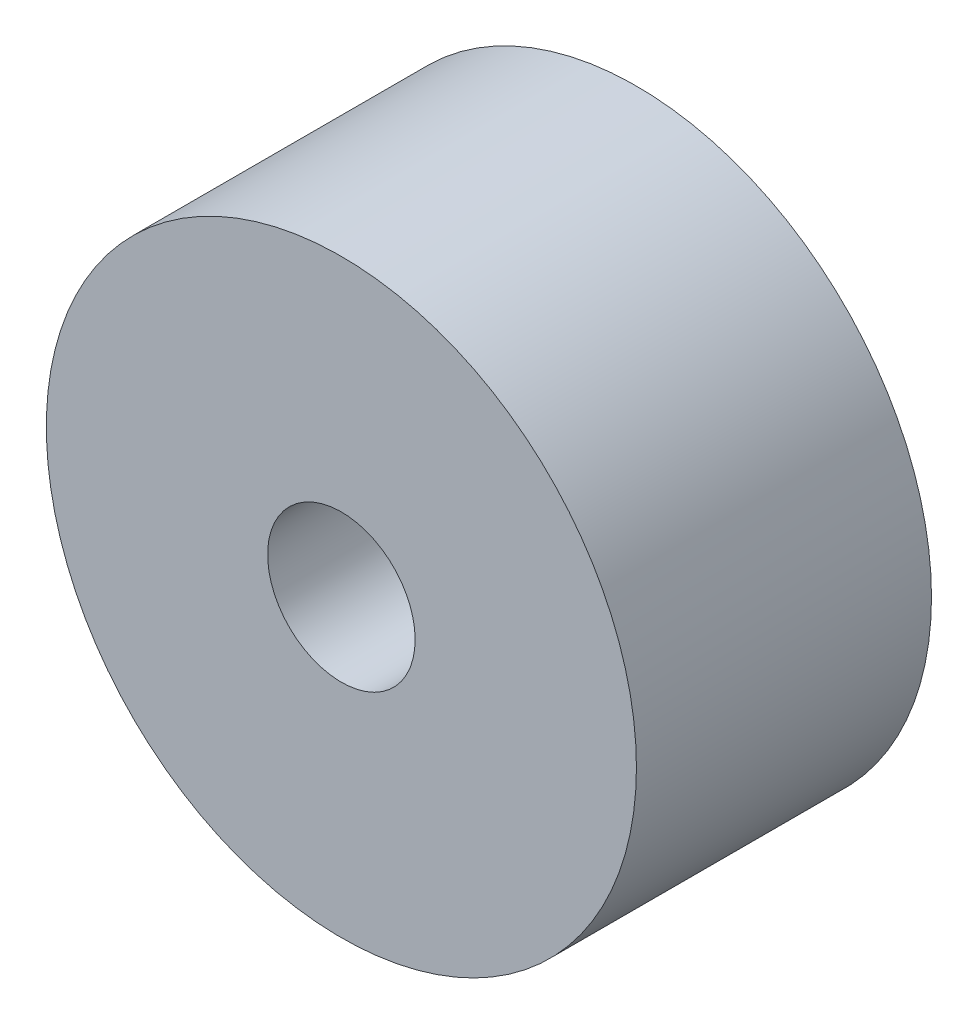
SolidWorks part; units mm, degrees
ref_plane "Front Plane" through (0, 0, 0) normal (0, 0, 1) x (1, 0, 0)
ref_plane "Top Plane" through (0, 0, 0) normal (0, 1, 0) x (1, 0, 0)
ref_plane "Right Plane" through (0, 0, 0) normal (1, 0, 0) x (0, 0, -1)
sketch "Sketch1" plane through (0, 0, 0) normal (0, 0, 1) x (1, 0, 0)
  circle A0 centre (0, 0) radius 10
  circle A1 centre (0, 0) radius 2.5
  dimension "D1" = 5
  dimension "D2" = 20
extrude "Boss-Extrude1" add sketch "Sketch1" along normal blind 10
